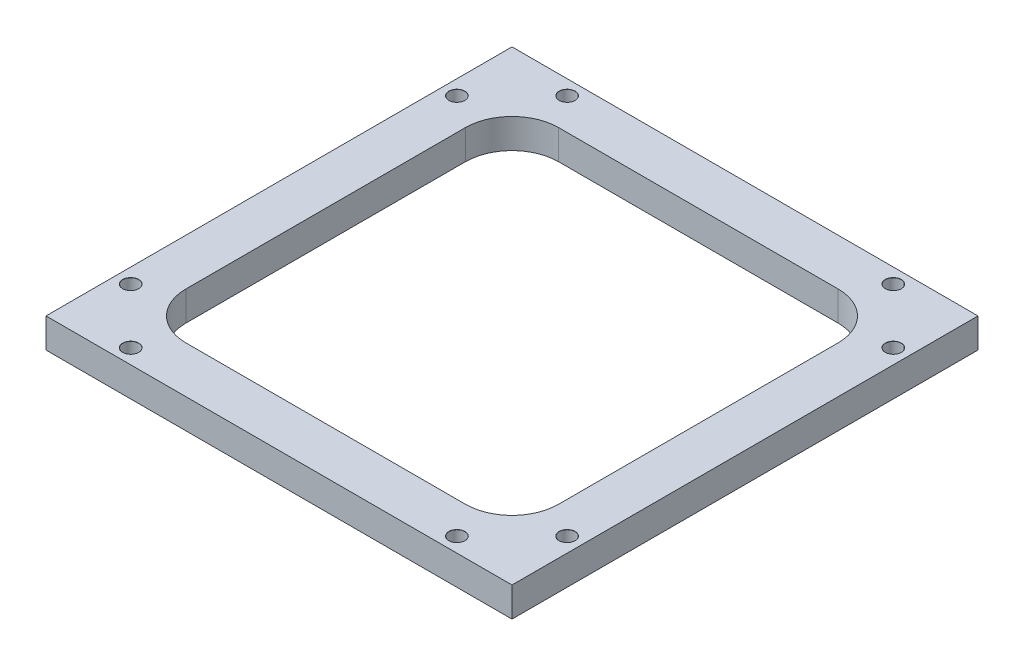
SolidWorks part; units mm, degrees
material "6061 Alloy"
ref_plane "Front Plane" through (0, 0, 0) normal (0, 0, 1) x (1, 0, 0)
ref_plane "Top Plane" through (0, 0, 0) normal (0, 1, 0) x (1, 0, 0)
ref_plane "Right Plane" through (0, 0, 0) normal (1, 0, 0) x (0, 0, -1)
sketch "Sketch1" plane through (0, 0, 0) normal (0, 1, 0) x (1, 0, 0)
  line L1 (-50, -50) -> (50, -50)
  line L2 (-50, -50) -> (-50, 50)
  line L3 (-50, 50) -> (50, 50)
  line L4 (50, -50) -> (50, 50)
  line L5 (-50, -50) -> (50, 50) construction
  line L6 (-50, 50) -> (50, -50) construction
extrude "Boss-Extrude3" add sketch "Sketch1" along normal blind 6.35
sketch "Sketch8" plane through (0, 6.35, 0) normal (0, 1, 0) x (1, 0, 0)
  line L0 (-50, -50) -> (-39.5, -50)
  line L1 (-50, -50) -> (50, -50) construction
  line L2 (-39.5, -50) -> (-39.5, -39.5)
  line L3 (50, -50) -> (39.5, -50)
  line L4 (39.5, -50) -> (39.5, -39.5)
  line L5 (50, 50) -> (39.5, 50)
  line L6 (-50, 50) -> (50, 50) construction
  line L7 (39.5, 50) -> (39.5, 39.5)
  line L8 (-50, 50) -> (-39.5, 50)
  line L9 (-50, -50) -> (-50, 50) construction
  line L10 (-39.5, 50) -> (-39.5, 39.5)
sketch "Sketch13" plane through (0, 6.35, 0) normal (0, 1, 0) x (1, 0, 0)
  line L1 (-50, -50) -> (-35, -50)
  line L2 (-50, -50) -> (50, -50) construction
  line L3 (-35, -50) -> (-35, -46.825)
  line L4 (-50, -50) -> (-50, -35)
  line L5 (-50, -50) -> (-50, 50) construction
  line L6 (-50, -35) -> (-46.825, -35)
  line L7 (-50, 50) -> (-35, 50)
  line L8 (-50, 50) -> (50, 50) construction
  line L9 (-35, 50) -> (-35, 46.825)
  line L10 (-50, 50) -> (-50, 35)
  line L11 (-50, 35) -> (-46.825, 35)
  line L13 (50, 50) -> (35, 50)
  line L14 (35, 50) -> (35, 46.825)
  line L15 (50, 50) -> (50, 35)
  line L16 (50, -50) -> (50, 50) construction
  line L17 (50, 35) -> (46.825, 35)
  line L18 (50, -50) -> (50, -35)
  line L19 (50, -35) -> (46.825, -35)
  line L20 (50, -50) -> (35, -50)
  line L21 (35, -50) -> (35, -46.825)
hole_wizard "M3 Clearance Hole1" positions "Sketch17" profile "Sketch18" hole size "M3" standard "ANSI Metric" end condition through all
sketch "Sketch17" plane through (0, 6.35, 0) normal (0, 1, 0) x (1, 0, 0)
  point P0 (-46.825, 35)
  point P3 (-35, 46.825)
  point P6 (35, 46.825)
  point P9 (46.825, 35)
  point P12 (46.825, -35)
  point P15 (35, -46.825)
  point P18 (-35, -46.825)
  point P21 (-46.825, -35)
sketch "Sketch18" plane through (-46.825, 6.35, -35) normal (1, 0, 0) x (0, 0, 1)
  line L0 (0, 0) -> (0, 6.35)
  line L1 (0, 6.35) -> (1.7, 6.35)
  line L2 (1.7, 6.35) -> (1.7, 0.025)
  line L3 (1.7, 0.025) -> (1.725, 0)
  line L5 (1.725, 0) -> (0, 0)
  line L6 (-1.7, 0.025) -> (-1.725, 0) construction
  line L11 (0, -6.35) -> (0, 107.95) construction
  dimension "Thru Hole Dia." = 3.4
  dimension "Thru Hole Depth" = 6.35
  dimension "Near C'Sink Dia." = 3.45
  dimension "Near C'Sink Angle" = 90
sketch "Sketch19" plane through (0, 6.35, 0) normal (0, 1, 0) x (1, 0, 0)
  line L1 (-30, -40) -> (30, -40)
  line L2 (-40, -30) -> (-40, 30)
  line L3 (-30, 40) -> (30, 40)
  line L4 (40, -30) -> (40, 30)
  line L5 (-40, -40) -> (40, 40) construction
  line L6 (-40, 40) -> (40, -40) construction
  arc A0 (-30, -40) -> (-40, -30) centre (-30, -30) cw
  arc A1 (40, -30) -> (30, -40) centre (30, -30) cw
  arc A2 (30, 40) -> (40, 30) centre (30, 30) cw
  arc A3 (-30, 40) -> (-40, 30) centre (-30, 30) ccw
  point P0 (0, 0)
  dimension "D1" = 10
extrude "Cut-Extrude1" cut sketch "Sketch19" against normal blind 10
